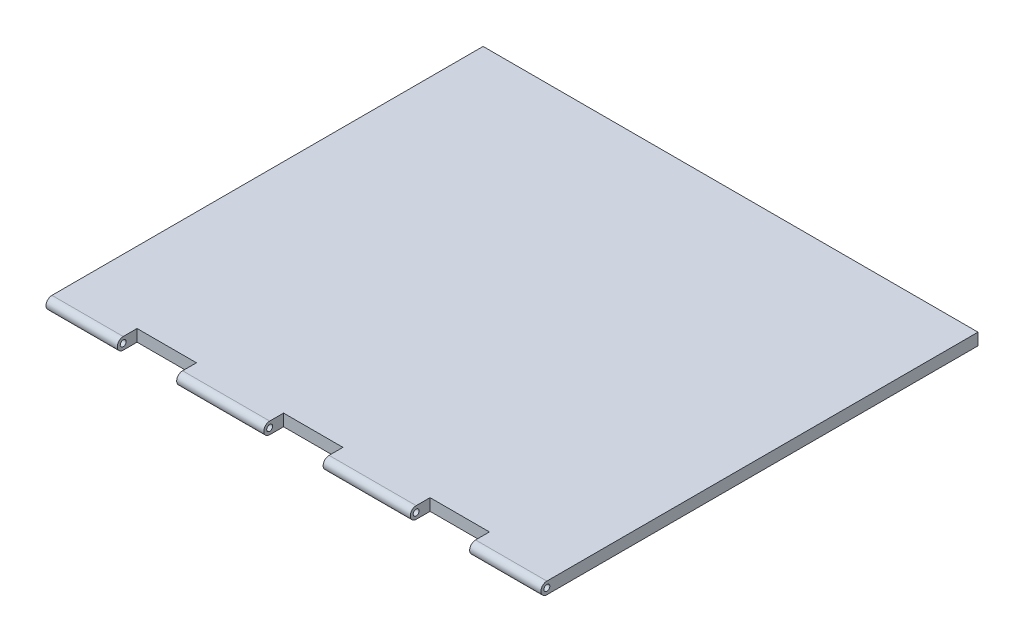
SolidWorks part; units mm, degrees
ref_plane "前视基准面" through (0, 0, 0) normal (0, 0, 1) x (1, 0, 0)
ref_plane "上视基准面" through (0, 0, 0) normal (0, 1, 0) x (1, 0, 0)
ref_plane "右视基准面" through (0, 0, 0) normal (1, 0, 0) x (0, 0, -1)
other "Configuration Table"
sketch "草图1" plane through (0, 0, 0) normal (0, 1, 0) x (1, 0, 0)
  line L1 (-93.9597, 64.3876) -> (156.0403, 64.3876)
  line L2 (-93.9597, 64.3876) -> (-93.9597, -156.4124)
  line L3 (-93.9597, -156.4124) -> (156.0403, -156.4124)
  line L4 (156.0403, 64.3876) -> (156.0403, -156.4124)
  dimension "D1" = 250
  dimension "D2" = 220.8
extrude "凸台-拉伸1" add sketch "草图1" along normal mid plane 6
sketch "草图2" plane through (0, 3, 0) normal (0, 1, 0) x (1, 0, 0)
  line L0 (-93.9597, -156.4124) -> (156.0403, -156.4124) construction
  line L1 (-27.9597, -156.4124) -> (-57.9597, -156.4124)
  line L2 (-27.9597, -156.4124) -> (-27.9597, -146.4124)
  line L3 (-27.9597, -146.4124) -> (-57.9597, -146.4124)
  line L4 (-57.9597, -156.4124) -> (-57.9597, -146.4124)
  line L5 (46.0403, -156.4124) -> (46.0403, -146.4124)
  line L6 (-93.9597, 64.3876) -> (-93.9597, -156.4124) construction
  line L7 (46.0403, -156.4124) -> (16.0403, -156.4124)
  line L8 (16.0403, -156.4124) -> (16.0403, -146.4124)
  line L9 (46.0403, -146.4124) -> (16.0403, -146.4124)
  line L10 (120.0403, -156.4124) -> (120.0403, -146.4124)
  line L11 (120.0403, -156.4124) -> (90.0403, -156.4124)
  line L12 (90.0403, -156.4124) -> (90.0403, -146.4124)
  line L13 (120.0403, -146.4124) -> (90.0403, -146.4124)
  line L14 (156.0403, -156.4124) -> (156.0403, 64.3876) construction
  dimension "D1" = 36
  dimension "D2" = 30
  dimension "D4" = 10
  dimension "D5" = 36
  dimension "D6" = 44
  dimension "D7" = 44
  dimension "D3" = 3
extrude "切除-拉伸1" cut sketch "草图2" against normal up to next
sketch "草图3" plane through (-93.9597, 0, 0) normal (-1, 0, 0) x (0, 0, 1)
  line L0 (-64.3876, -3) -> (156.4124, -3) construction
  line L1 (153.4124, 3) -> (147.4124, 3)
  line L4 (147.4124, 3) -> (147.4124, -3)
  line L5 (156.4124, 3) -> (156.4124, -3) construction
  line L6 (147.4124, -3) -> (153.4124, -3)
  line L7 (153.4124, 3) -> (156.4124, 3)
  line L8 (156.4124, 3) -> (156.4124, 0)
  line L9 (153.4124, -3) -> (156.4124, -3)
  line L10 (156.4124, -3) -> (156.4124, 0)
  arc A0 (156.4124, 0) -> (153.4124, 3) centre (153.4124, 0) ccw
  arc A1 (153.4124, -3) -> (156.4124, 0) centre (153.4124, 0) ccw
  circle A2 centre (153.4124, 0) radius 1.5
  point P9 (156.4124, 3)
  line M9 (-64.3876, -3) -> (156.4124, -3)
  line M10 (156.4124, -3) -> (156.4124, 3)
  line M11 (156.4124, 3) -> (-64.3876, 3)
  dimension "D3" = 3
  dimension "D2" = 3
  dimension "D1" = 9
extrude "切除-拉伸2" cut sketch "草图3" against normal through all contours A2 | A0 M10 M11 | A1 M9 M10
